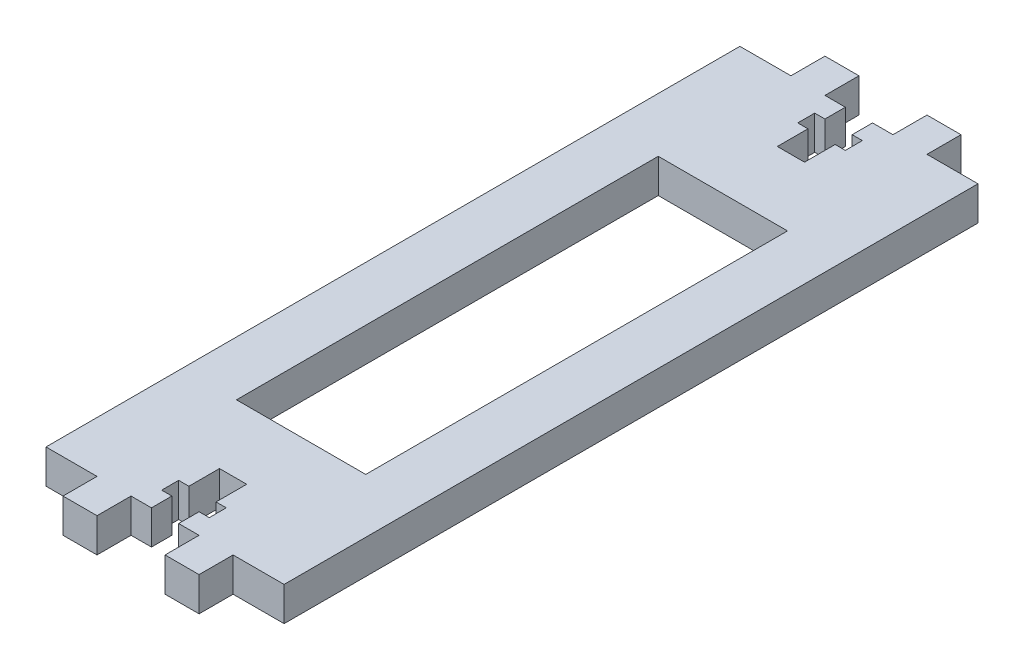
SolidWorks part; units mm, degrees
ref_plane "Front Plane" through (0, 0, 0) normal (0, 0, 1) x (1, 0, 0)
ref_plane "Top Plane" through (0, 0, 0) normal (0, 1, 0) x (1, 0, 0)
ref_plane "Right Plane" through (0, 0, 0) normal (1, 0, 0) x (0, 0, -1)
sketch "Sketch1" plane through (0, 0, 0) normal (0, 1, 0) x (1, 0, 0)
  line L0 (15.956, 19.0395) -> (15.956, -0.9605) construction
  line L1 (6.456, 19.0395) -> (25.456, 19.0395)
  line L2 (-1.544, 19.0395) -> (-1.544, -0.9605)
  line L3 (-1.544, -0.9605) -> (5.956, -0.9605)
  line L4 (33.456, 19.0395) -> (33.456, -0.9605)
  line L5 (25.956, -0.9605) -> (33.456, -0.9605)
  line L7 (25.956, -0.9605) -> (25.956, -5.9605)
  line L8 (25.956, -5.9605) -> (20.956, -5.9605)
  line L9 (20.956, -0.9605) -> (20.956, -5.9605)
  line L10 (5.956, -0.9605) -> (5.956, -5.9605)
  line L11 (5.956, -5.9605) -> (10.956, -5.9605)
  line L12 (10.956, -0.9605) -> (10.956, -5.9605)
  line L13 (10.956, -0.9605) -> (13.956, -0.9605)
  line L14 (17.956, -0.9605) -> (20.956, -0.9605)
  line L16 (13.956, -0.9605) -> (13.956, 2.0395)
  line L17 (13.956, 9.0395) -> (17.956, 9.0395)
  line L18 (17.956, -0.9605) -> (17.956, 2.0395)
  line L19 (17.956, 2.0395) -> (19.456, 2.0395)
  line L21 (17.956, 4.5395) -> (19.456, 4.5395)
  line L22 (19.456, 2.0395) -> (19.456, 4.5395)
  line L23 (13.956, 2.0395) -> (12.456, 2.0395)
  line L24 (12.456, 2.0395) -> (12.456, 4.5395)
  line L25 (13.956, 4.5395) -> (12.456, 4.5395)
  line L26 (13.956, 4.5395) -> (13.956, 9.0395)
  line L27 (17.956, 4.5395) -> (17.956, 9.0395)
  line L30 (-1.544, 19.0395) -> (-1.544, 81.0395)
  line L32 (6.456, 19.0395) -> (6.456, 81.0395)
  line L33 (25.456, 19.0395) -> (25.456, 81.0395)
  line L34 (33.456, 19.0395) -> (33.456, 81.0395)
  line L35 (-1.544, 50.0395) -> (33.456, 50.0395) construction
  line L36 (13.956, 4.5395) -> (13.956, 9.0395)
  line L37 (17.956, 4.5395) -> (17.956, 9.0395)
  line L38 (17.956, 4.5395) -> (19.456, 4.5395)
  line L39 (19.456, 2.0395) -> (19.456, 4.5395)
  line L40 (17.956, 2.0395) -> (19.456, 2.0395)
  line L41 (12.456, 2.0395) -> (12.456, 4.5395)
  line L42 (13.956, 4.5395) -> (12.456, 4.5395)
  line L43 (13.956, 2.0395) -> (12.456, 2.0395)
  line L44 (13.956, -0.9605) -> (13.956, 2.0395)
  line L45 (17.956, -0.9605) -> (17.956, 2.0395)
  line L46 (13.956, -0.9605) -> (10.956, -0.9605)
  line L47 (20.956, -0.9605) -> (17.956, -0.9605)
  line L48 (20.956, -0.9605) -> (20.956, -5.9605)
  line L49 (25.956, -5.9605) -> (20.956, -5.9605)
  line L50 (25.956, -0.9605) -> (25.956, -5.9605)
  line L51 (10.956, -0.9605) -> (10.956, -5.9605)
  line L52 (5.956, -5.9605) -> (10.956, -5.9605)
  line L53 (5.956, -0.9605) -> (5.956, -5.9605)
  line L54 (5.956, -0.9605) -> (-1.544, -0.9605)
  line L55 (-1.544, 19.0395) -> (-1.544, -0.9605)
  line L56 (33.456, -0.9605) -> (25.956, -0.9605)
  line L57 (33.456, 19.0395) -> (33.456, -0.9605)
  line L58 (25.456, 19.0395) -> (6.456, 19.0395)
  line L59 (15.956, 81.0395) -> (15.956, 101.0395) construction
  line L60 (25.456, 81.0395) -> (6.456, 81.0395)
  line L61 (33.456, 81.0395) -> (33.456, 101.0395)
  line L62 (33.456, 101.0395) -> (25.956, 101.0395)
  line L63 (-1.544, 81.0395) -> (-1.544, 101.0395)
  line L64 (5.956, 101.0395) -> (-1.544, 101.0395)
  line L65 (5.956, 101.0395) -> (5.956, 106.0395)
  line L66 (5.956, 106.0395) -> (10.956, 106.0395)
  line L67 (10.956, 101.0395) -> (10.956, 106.0395)
  line L68 (25.956, 101.0395) -> (25.956, 106.0395)
  line L69 (25.956, 106.0395) -> (20.956, 106.0395)
  line L70 (20.956, 101.0395) -> (20.956, 106.0395)
  line L71 (20.956, 101.0395) -> (17.956, 101.0395)
  line L72 (13.956, 101.0395) -> (10.956, 101.0395)
  line L73 (17.956, 101.0395) -> (17.956, 98.0395)
  line L74 (13.956, 101.0395) -> (13.956, 98.0395)
  line L75 (13.956, 98.0395) -> (12.456, 98.0395)
  line L76 (13.956, 95.5395) -> (12.456, 95.5395)
  line L77 (12.456, 98.0395) -> (12.456, 95.5395)
  line L78 (17.956, 98.0395) -> (19.456, 98.0395)
  line L79 (19.456, 98.0395) -> (19.456, 95.5395)
  line L80 (17.956, 95.5395) -> (19.456, 95.5395)
  line L81 (17.956, 95.5395) -> (17.956, 91.0395)
  line L82 (13.956, 95.5395) -> (13.956, 91.0395)
  line L83 (17.956, 95.5395) -> (17.956, 91.0395)
  line L84 (13.956, 95.5395) -> (13.956, 91.0395)
  line L85 (13.956, 95.5395) -> (12.456, 95.5395)
  line L86 (12.456, 98.0395) -> (12.456, 95.5395)
  line L87 (13.956, 98.0395) -> (12.456, 98.0395)
  line L88 (19.456, 98.0395) -> (19.456, 95.5395)
  line L89 (17.956, 95.5395) -> (19.456, 95.5395)
  line L90 (17.956, 98.0395) -> (19.456, 98.0395)
  line L91 (17.956, 101.0395) -> (17.956, 98.0395)
  line L92 (13.956, 91.0395) -> (17.956, 91.0395)
  line L93 (13.956, 101.0395) -> (13.956, 98.0395)
  line L94 (17.956, 101.0395) -> (20.956, 101.0395)
  line L95 (10.956, 101.0395) -> (13.956, 101.0395)
  line L96 (10.956, 101.0395) -> (10.956, 106.0395)
  line L97 (5.956, 106.0395) -> (10.956, 106.0395)
  line L98 (5.956, 101.0395) -> (5.956, 106.0395)
  line L99 (20.956, 101.0395) -> (20.956, 106.0395)
  line L100 (25.956, 106.0395) -> (20.956, 106.0395)
  line L101 (25.956, 101.0395) -> (25.956, 106.0395)
  line L102 (25.956, 101.0395) -> (33.456, 101.0395)
  line L103 (33.456, 81.0395) -> (33.456, 101.0395)
  line L104 (-1.544, 101.0395) -> (5.956, 101.0395)
  line L105 (-1.544, 81.0395) -> (-1.544, 101.0395)
  line L106 (6.456, 81.0395) -> (25.456, 81.0395)
  point P10 (20.956, -3.4605)
  point P59 (0, 0)
  point P60 (0, 0)
  point P61 (0, 0)
  point P62 (0, 0)
  point P63 (0, 0)
  point P64 (0, 0)
  point P65 (0, 0)
  point P66 (0, 0)
  dimension "D1" = 20
  dimension "D2" = 35
  dimension "D3" = 5
  dimension "D4" = 5
  dimension "D5" = 3
  dimension "D6" = 10
  dimension "D7" = 2.5
  dimension "D8" = 3
  dimension "D9" = 1.5
  dimension "D10" = 62
  dimension "D11" = 8
extrude "Boss-Extrude1" add sketch "Sketch1" along normal blind 5 contours L92 L82 L76 L77 L75 L74 L72 L67 L66 L65 L64 L63 L30 L2 L3 L10 L11 L12 L13 L16 L23 L24 L25 L26 L17 L27 L21 L22 L19 L18 L14 L9 L8 L7 L5 L4 L34 L61 L62 L68 L69 L70 L71 L73 L78 L79 L80 L81 L60 L33
